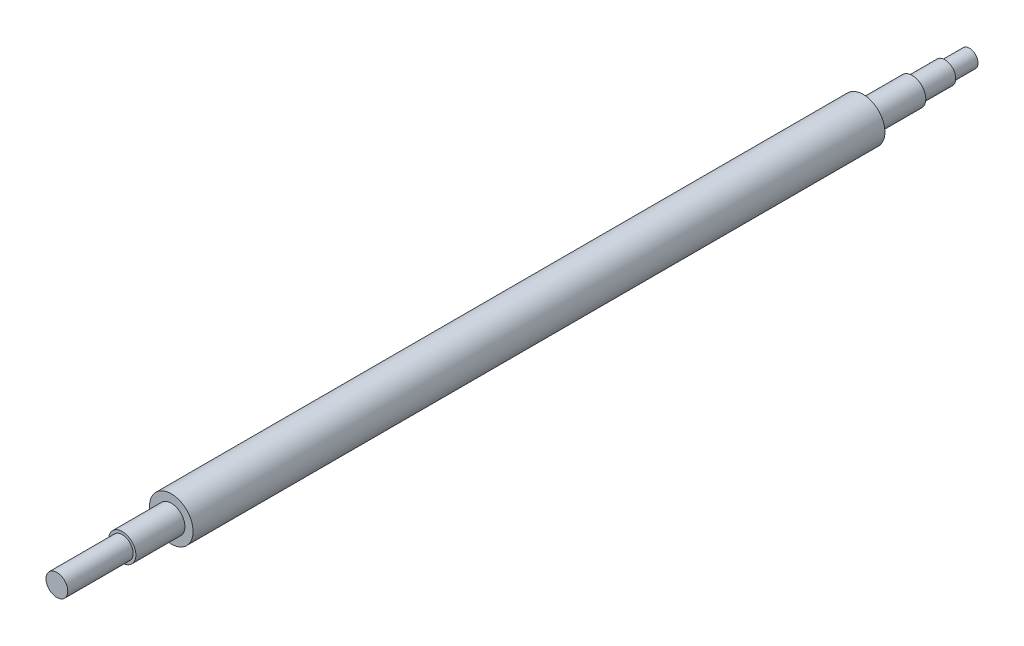
SolidWorks part; units mm, degrees
ref_plane "前视基准面" through (0, 0, 0) normal (0, 0, 1) x (1, 0, 0)
ref_plane "上视基准面" through (0, 0, 0) normal (0, 1, 0) x (1, 0, 0)
ref_plane "右视基准面" through (0, 0, 0) normal (1, 0, 0) x (0, 0, -1)
sketch "草图1" plane through (0, 0, 0) normal (0, 0, 1) x (1, 0, 0)
  circle A0 centre (0, 0) radius 8
  dimension "D1" = 16
extrude "凸台-拉伸1" add sketch "草图1" along normal blind 254
cosmetic thread "装饰螺纹线1" parameters "D2"=15.999
sketch "草图2" plane through (0, 0, 254) normal (0, 0, 1) x (1, 0, 0)
  circle A0 centre (0, 0) radius 5
  dimension "D1" = 10
extrude "凸台-拉伸2" add sketch "草图2" along normal blind 18 separate body
sketch "草图4" plane through (0, 0, 0) normal (0, 0, -1) x (-1, 0, 0)
  circle A0 centre (0, 0) radius 5
  dimension "D1" = 10
extrude "凸台-拉伸3" add sketch "草图4" along normal blind 18 separate body
sketch "草图5" plane through (0, 0, 272) normal (0, 0, 1) x (1, 0, 0)
  circle A0 centre (0, 0) radius 4
  dimension "D1" = 8
extrude "凸台-拉伸4" add sketch "草图5" along normal blind 24
sketch "草图9" plane through (0, 0, -18) normal (0, 0, -1) x (-1, 0, 0)
  circle A0 centre (0, 0) radius 4
  dimension "D1" = 8
extrude "凸台-拉伸5" add sketch "草图9" along normal blind 12
sketch "草图10" plane through (0, 0, -30) normal (0, 0, -1) x (-1, 0, 0)
  circle A2 centre (0, 0) radius 3.175
  dimension "D1" = 6.35
extrude "凸台-拉伸6" add sketch "草图10" along normal blind 9
